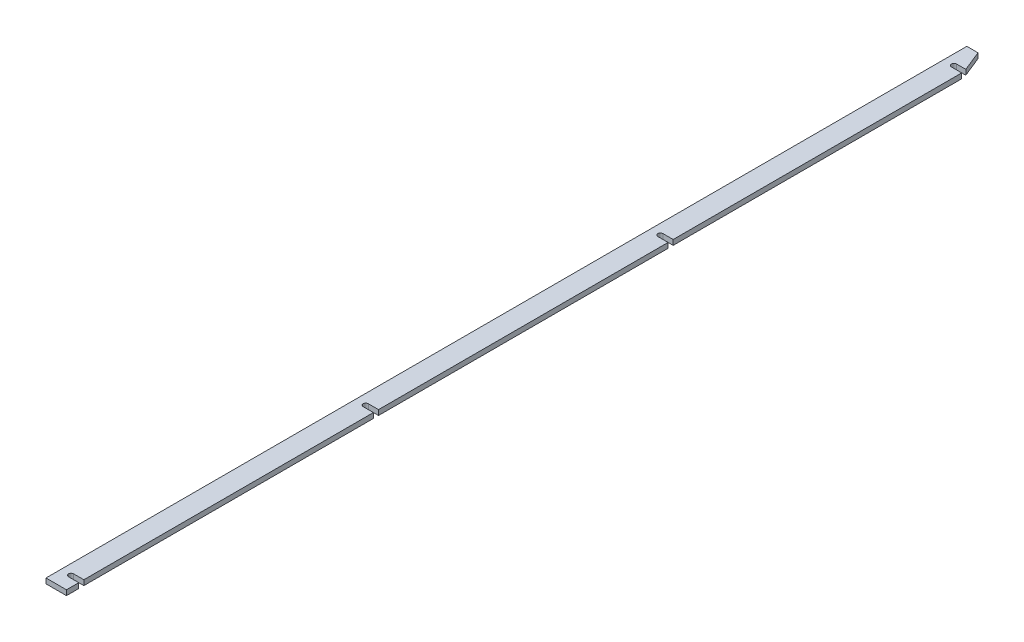
SolidWorks part; units mm, degrees
material "G10"
ref_plane "Front Plane" through (0, 0, 0) normal (0, 0, 1) x (1, 0, 0)
ref_plane "Top Plane" through (0, 0, 0) normal (0, 1, 0) x (1, 0, 0)
ref_plane "Right Plane" through (0, 0, 0) normal (1, 0, 0) x (0, 0, -1)
sketch "Sketch1" plane through (0, 0, 0) normal (0, 1, 0) x (1, 0, 0)
  line L0 (-3.175, 142.875) -> (3.175, -142.875) construction
  line L1 (3.175, -142.875) -> (-3.175, -142.875)
  line L2 (3.175, -142.875) -> (3.175, 142.875)
  line L3 (3.175, 142.875) -> (-3.175, 142.875)
  line L4 (-3.175, -142.875) -> (-3.175, 142.875)
  point P8 (0, 0)
extrude "Boss-Extrude1" add sketch "Sketch1" along normal blind 1.5875
sketch "Sketch2" plane through (0, 1.5875, 0) normal (0, 1, 0) x (1, 0, 0)
  line L0 (3.175, -142.875) -> (3.175, 142.875) construction
  line L1 (3.175, -139.065) -> (0, -139.065)
  line L2 (3.175, -139.065) -> (3.175, -137.4775)
  line L3 (3.175, -137.4775) -> (0, -137.4775)
  line L5 (-3.175, -142.875) -> (3.175, -142.875) construction
  line L6 (0, -139.065) -> (0, -203.5211) construction
  line L18 (0, 161.4311) -> (0, -137.4775) construction
  arc A0 (0, -139.065) -> (0, -137.4775) centre (0, -138.2713) cw
extrude "Cut-Extrude1" cut sketch "Sketch2" against normal up to next
pattern_linear "LPattern1" count 3 spacing 91.44 along (0, 0, -1) of "Cut-Extrude1"
sketch "Sketch4" plane through (0, 1.5875, 0) normal (0, 1, 0) x (-1, 0, 0)
  line L0 (-2.8545, -136.525) -> (0, -136.525)
  line L1 (-3.175, -45.4025) -> (-3.175, -142.875) construction
  line L2 (-3.175, -142.875) -> (3.175, -142.875) construction
  line L3 (0, -134.9375) -> (-3.175, -134.9375)
  line L4 (-3.175, -134.9375) -> (-3.175, -142.875)
  line L5 (-3.175, -142.875) -> (-0.2909, -142.875)
  line L6 (-0.2909, -142.875) -> (-2.8545, -136.525)
  arc A0 (0, -136.525) -> (0, -134.9375) centre (0, -135.7312) ccw
extrude "Cut-Extrude3" cut sketch "Sketch4" against normal blind 2.54
